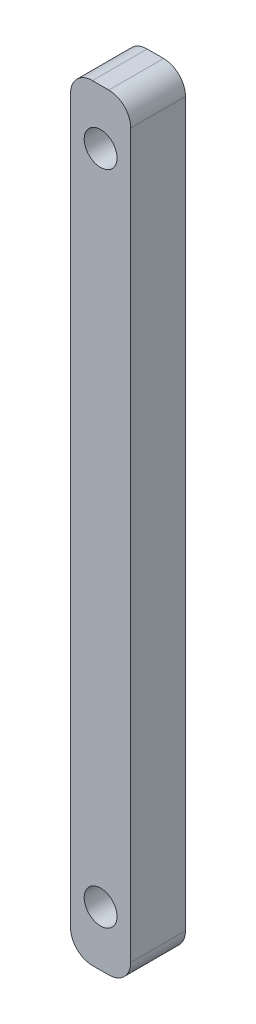
SolidWorks part; units mm, degrees
ref_plane "前视基准面" through (0, 0, 0) normal (0, 0, 1) x (1, 0, 0)
ref_plane "上视基准面" through (0, 0, 0) normal (0, 1, 0) x (1, 0, 0)
ref_plane "右视基准面" through (0, 0, 0) normal (1, 0, 0) x (0, 0, -1)
sketch "草图1" plane through (0, 0, 0) normal (0, 0, 1) x (1, 0, 0)
  line L1 (2.75, -35) -> (-2.75, -35)
  line L2 (2.75, -35) -> (2.75, 35)
  line L3 (2.75, 35) -> (-2.75, 35)
  line L4 (-2.75, -35) -> (-2.75, 35)
  line L5 (2.75, -35) -> (-2.75, 35) construction
  line L6 (2.75, 35) -> (-2.75, -35) construction
  point P0 (0, 0)
  dimension "D1" = 5.5
  dimension "D2" = 70
extrude "凸台-拉伸1" add sketch "草图1" along normal blind 5
sketch "草图2" plane through (0, 0, 5) normal (0, 0, 1) x (1, 0, 0)
  circle A0 centre (0, 30) radius 1.5
  circle A1 centre (0, -30) radius 1.5
  dimension "D3" = 3
  dimension "D4" = 3
  dimension "D1" = 30
  dimension "D2" = 30
extrude "切除-拉伸1" cut sketch "草图2" against normal through all
fillet "圆角1" radius 2 4 edges at (-2.75, -35, 2.5) (2.75, -35, 2.5) (2.75, 35, 2.5) (-2.75, 35, 2.5)
